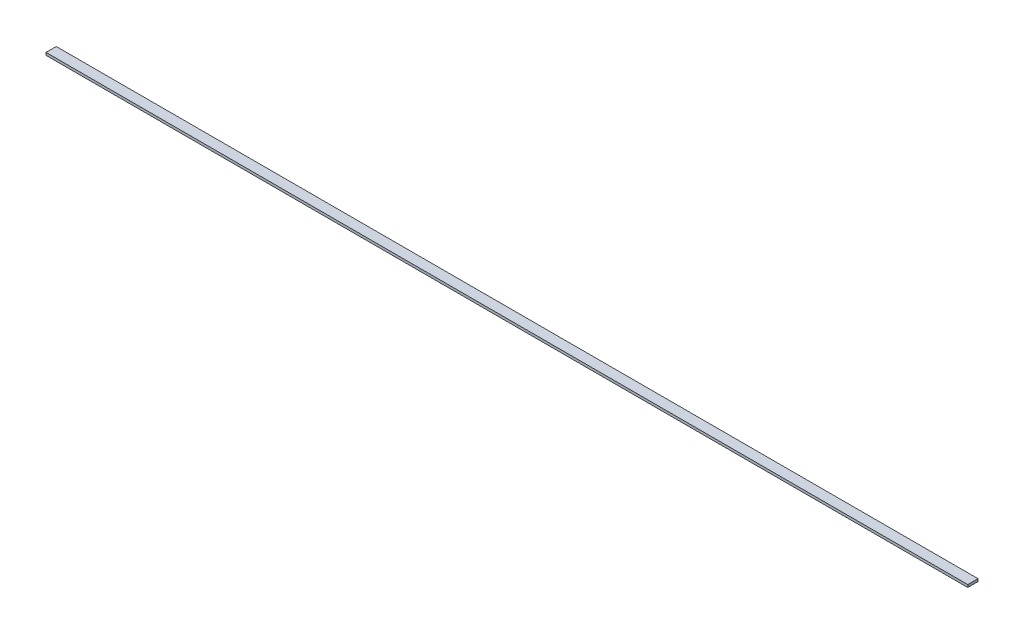
SolidWorks part; units mm, degrees
ref_plane "Front Plane" through (0, 0, 0) normal (0, 0, 1) x (1, 0, 0)
ref_plane "Top Plane" through (0, 0, 0) normal (0, 1, 0) x (1, 0, 0)
ref_plane "Right Plane" through (0, 0, 0) normal (1, 0, 0) x (0, 0, -1)
sketch "Sketch1" plane through (0, 0, 0) normal (0, 1, 0) x (1, 0, 0)
  line L1 (-1143, -12.7) -> (1143, -12.7)
  line L2 (-1143, -12.7) -> (-1143, 12.7)
  line L3 (-1143, 12.7) -> (1143, 12.7)
  line L4 (1143, -12.7) -> (1143, 12.7)
  line L5 (-1143, -12.7) -> (1143, 12.7) construction
  line L6 (-1143, 12.7) -> (1143, -12.7) construction
  point P0 (0, 0)
  dimension "D1" = 2286
  dimension "D2" = 25.4
extrude "Boss-Extrude1" add sketch "Sketch1" along normal blind 6.35
equation "\"horizontal-component-length\"= 90in'= \"railing-hypotenuse\" - \"railing-hypotenuse-horizontal-component-length-difference\""
equation "\"horizontal-component-width\"= 1in"
equation "\"D1@Sketch1\"=\"horizontal-component-length\""
equation "\"D2@Sketch1\"=\"horizontal-component-width\""
equation "\"material-thickness\"= .25in"
equation "\"D1@Boss-Extrude1\"=\"material-thickness\""
equation "\"railing-hypotenuse\"= 92in"
equation "\"railing-hypotenuse-horizontal-component-length-difference\"= 1.75in"
